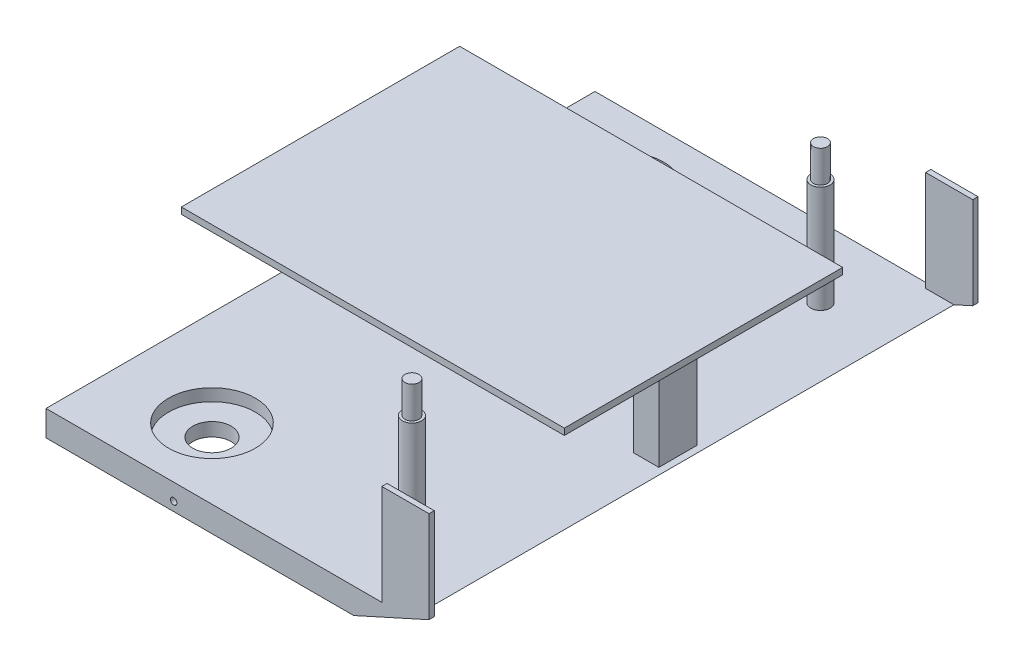
SolidWorks part; units mm, degrees
material "PBT General Purpose"
ref_plane "Front Plane" through (0, 0, 0) normal (0, 0, 1) x (1, 0, 0)
ref_plane "Top Plane" through (0, 0, 0) normal (0, 1, 0) x (1, 0, 0)
ref_plane "Right Plane" through (0, 0, 0) normal (1, 0, 0) x (0, 0, -1)
sketch "Sketch2" plane through (0, 0, 0) normal (0, 1, 0) x (1, 0, 0)
  line L1 (-150, -215) -> (150, -215)
  line L2 (-150, -215) -> (-150, 215)
  line L3 (-150, 215) -> (150, 215)
  line L4 (150, -215) -> (150, 215)
  line L5 (-150, -215) -> (150, 215) construction
  line L6 (-150, 215) -> (150, -215) construction
  point P0 (0, 0)
  dimension "D1" = 300
  dimension "D2" = 430
extrude "Boss-Extrude1" add sketch "Sketch2" along normal blind 20
sketch "Sketch3" plane through (0, 20, 0) normal (0, 1, 0) x (1, 0, 0)
  line L0 (0, 0) -> (233.8043, 0) construction
  line L1 (0, 0) -> (0, 255.0295) construction
  circle A0 centre (-75, 160) radius 15
  circle A1 centre (-75, 160) radius 34
  circle A4 centre (-75, -160) radius 15
  circle A5 centre (-75, -160) radius 34
  circle A6 centre (101.2853, 160) radius 9.5009
  dimension "D1" = 30
  dimension "D2" = 68
  dimension "D3" = 75
  dimension "D4" = 160
extrude "Cut-Extrude1" cut sketch "Sketch3" against normal blind 20 contours A4 | A0
sketch "Sketch4" plane through (0, 20, 0) normal (0, 1, 0) x (1, 0, 0)
  line L0 (0, 0) -> (198.5377, 0) construction
  circle A0 centre (-75, 160) radius 34
  circle A1 centre (-75, -160) radius 34
  dimension "D1" = 68
extrude "Cut-Extrude2" cut sketch "Sketch4" against normal blind 9.5
sketch "Sketch5" plane through (0, 20, 0) normal (0, 1, 0) x (1, 0, 0)
  line L0 (0, 0) -> (218.7833, 0) construction
  circle A0 centre (81.6356, 160) radius 7.5
  circle A3 centre (81.6356, -160) radius 7.5
  dimension "D1" = 15
extrude "Boss-Extrude2" add sketch "Sketch5" along normal blind 108.65
sketch "Sketch6" plane through (0, 128.65, 0) normal (0, 1, 0) x (1, 0, 0)
  line L0 (0, 0) -> (265.2012, 0) construction
  circle A0 centre (81.6356, -160) radius 5.5
  circle A1 centre (81.6356, -160) radius 7.5
  circle A2 centre (81.6356, 160) radius 7.5
  circle A3 centre (81.6356, 160) radius 5.5
  dimension "D1" = 11
extrude "Cut-Extrude4" cut sketch "Sketch6" against normal blind 25
sketch "Sketch7" plane through (0, 20, 0) normal (0, 1, 0) x (1, 0, 0)
  line L1 (110, -15) -> (130, -15)
  line L2 (110, -15) -> (110, 15)
  line L3 (110, 15) -> (130, 15)
  line L4 (130, -15) -> (130, 15)
  line L5 (110, -15) -> (130, 15) construction
  line L6 (110, 15) -> (130, -15) construction
  line L7 (0, 0) -> (0, 86.5607) construction
  line L8 (-110, 15) -> (-130, 15)
  line L9 (-130, -15) -> (-130, 15)
  line L10 (-110, -15) -> (-130, -15)
  line L11 (-110, -15) -> (-110, 15)
  line L13 (150, -215) -> (150, 215) construction
  point P0 (120, 0)
  dimension "D1" = 20
  dimension "D2" = 30
  dimension "D3" = 40
extrude "Boss-Extrude3" add sketch "Sketch7" along normal blind 78.65
sketch "Sketch8" plane through (0, 98.65, 0) normal (0, 1, 0) x (1, 0, 0)
  line L0 (150, -215) -> (150, 215) construction
  line L1 (150, -109) -> (-150, -109)
  line L2 (150, -109) -> (150, 109)
  line L3 (150, 109) -> (-150, 109)
  line L4 (-150, -109) -> (-150, 109)
  line L5 (150, -109) -> (-150, 109) construction
  line L6 (150, 109) -> (-150, -109) construction
  point P0 (0, 0)
  dimension "D1" = 218
extrude "Boss-Extrude4" add sketch "Sketch8" along normal blind 5
sketch "Sketch12" plane through (0, 98.65, 0) normal (0, -1, 0) x (1, 0, 0)
  line L0 (150, 109) -> (150, -109) construction
  line L2 (144.5, 80.9812) -> (144.5, 51.3648) construction
  line L3 (0, 0) -> (200.8333, 0) construction
  circle A0 centre (144.5, 80.9812) radius 2.5
  circle A1 centre (144.5, 36.9812) radius 2.5
  circle A2 centre (144.5, -80.9812) radius 2.5
  circle A3 centre (144.5, -36.9812) radius 2.5
  dimension "D1" = 5.5
  dimension "D2" = 5
  dimension "D3" = 2
extrude "Cut-Extrude7" cut sketch "Sketch12" against normal blind 4
sketch "Sketch13" plane through (0, 20, 0) normal (0, 1, 0) x (1, 0, 0)
  line L1 (150, -215) -> (113.0476, -215)
  line L2 (150, -215) -> (150, -210.8918)
  line L3 (150, -210.8918) -> (113.0476, -210.8918)
  line L4 (113.0476, -215) -> (113.0476, -210.8918)
extrude "Boss-Extrude5" add sketch "Sketch13" along normal blind 78.6
sketch "Sketch15" plane through (0, 20, 0) normal (0, 1, 0) x (1, 0, 0)
  line L0 (0, 0) -> (294.7774, 0) construction
  line L5 (150, 215) -> (150, 210.8918)
  line L6 (150, 215) -> (113.0476, 215)
  line L7 (113.0476, 215) -> (113.0476, 210.8918)
  line L8 (150, 210.8918) -> (113.0476, 210.8918)
extrude "Boss-Extrude6" add sketch "Sketch15" along normal blind 78.65
sketch "Sketch16" plane through (0, 0, 215) normal (0, 0, 1) x (1, 0, 0)
  line L0 (90.9867, 0) -> (150, 26.6632)
  line L1 (-150, 0) -> (150, 0) construction
  line L2 (150, 98.6) -> (150, 0) construction
  line L3 (150, 26.6632) -> (150, 0)
  line L4 (150, 0) -> (90.9867, 0)
extrude "Cut-Extrude8" cut sketch "Sketch16" against normal through all
sketch "Sketch17" plane through (0, 0, 215) normal (0, 0, 1) x (1, 0, 0)
  line L1 (-150, 20) -> (113.0476, 20) construction
  line L2 (-150, 20) -> (-150, 0) construction
  circle A0 centre (-50, 7) radius 2.5
  dimension "D2" = 5
  dimension "D1" = 13
  dimension "D3" = 100
extrude "Cut-Extrude9" cut sketch "Sketch17" against normal through all
